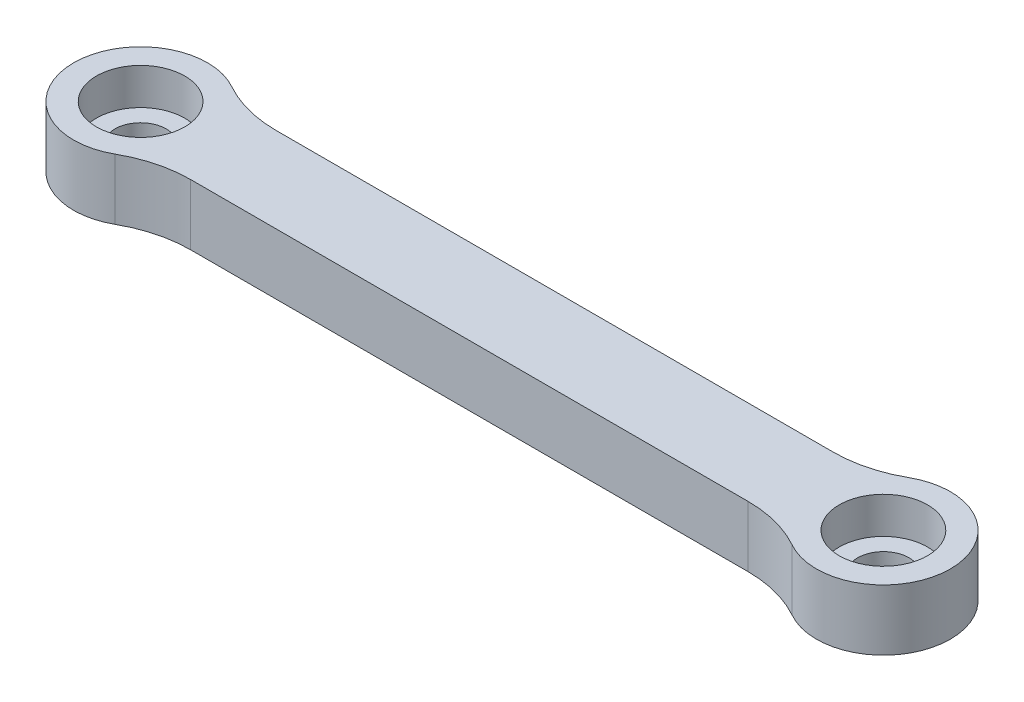
SolidWorks part; units mm, degrees
ref_plane "Front Plane" through (0, 0, 0) normal (0, 0, 1) x (1, 0, 0)
ref_plane "Top Plane" through (0, 0, 0) normal (0, 1, 0) x (1, 0, 0)
ref_plane "Right Plane" through (0, 0, 0) normal (1, 0, 0) x (0, 0, -1)
sketch "Sketch1" plane through (0, 0, 0) normal (0, 1, 0) x (1, 0, 0)
  line L1 (-30.5, -3.5) -> (-30.5, -14.3154) construction
  line L6 (-65.5, 3.5) -> (-65.2622, 3.4762) construction
  line L7 (-65.5, -3.5) -> (-65.2622, -3.4762) construction
  line L8 (-56.7574, -3.5) -> (-4.2426, -3.5)
  line L10 (-57.5, 0) -> (-61, 0) construction
  line L12 (-56.7574, 3.5) -> (-4.2426, 3.5)
  circle A1 centre (-61, 0) radius 2.1
  arc A6 (-58.9632, -2.8463) -> (-57.5, 0) centre (-61, 0) ccw construction
  arc A7 (-56.7574, 3.5) -> (-56.7574, -3.5) centre (-61, 0) ccw
  circle A8 centre (0, 0) radius 2.1
  arc A9 (-4.2426, 3.5) -> (-4.2426, -3.5) centre (0, 0) cw
  point P5 (-30.5, 0)
  point P9 (-30.5, 3.5)
  dimension "D3" = 4.2
  dimension "D7" = 7
  dimension "D8" = 2
extrude "Boss-Extrude1" add sketch "Sketch1" along normal blind 5
sketch "Sketch2" plane through (0, 5, 0) normal (0, 1, 0) x (1, 0, 0)
  circle A0 centre (-61, 0) radius 3.625
  circle A1 centre (0, 0) radius 3.625
  dimension "D1" = 7.25
  dimension "D2" = 7.25
extrude "Cut-Extrude1" cut sketch "Sketch2" against normal blind 3
fillet "Fillet1" radius 10 4 edges at (-56.7574, 2.5, 3.5) (-4.2426, 2.5, 3.5) (-4.2426, 2.5, -3.5) (-56.7574, 2.5, -3.5)
